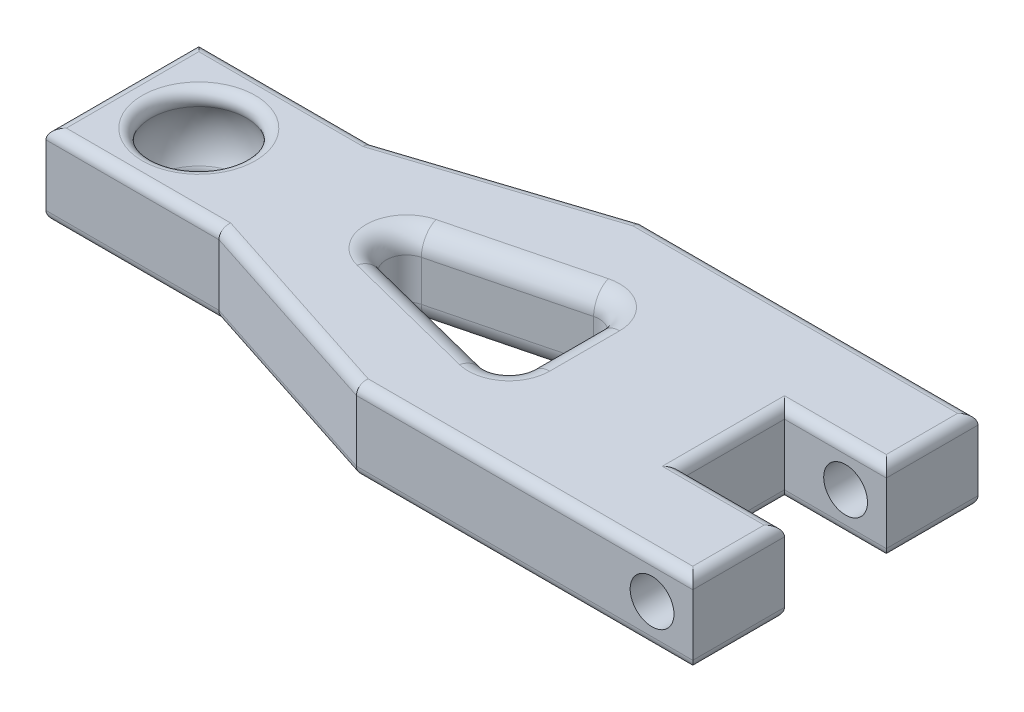
SolidWorks part; units mm, degrees
ref_plane "Front Plane" through (0, 0, 0) normal (0, 0, 1) x (1, 0, 0)
ref_plane "Top Plane" through (0, 0, 0) normal (0, 1, 0) x (1, 0, 0)
ref_plane "Right Plane" through (0, 0, 0) normal (1, 0, 0) x (0, 0, -1)
sketch "Sketch1" plane through (0, 0, 0) normal (0, 1, 0) x (1, 0, 0)
  line L1 (35, -14) -> (-35, -14)
  line L2 (35, -14) -> (35, 14)
  line L3 (35, 14) -> (-35, 14)
  line L4 (-35, -14) -> (-35, 14)
  dimension "D1" = 70
  dimension "D2" = 28
  dimension "D3" = 14
  dimension "D4" = 14
  dimension "D5" = 35
extrude "Boss-Extrude1" add sketch "Sketch1" along normal blind 8
sketch "Sketch2" plane through (0, 8, 0) normal (0, 1, 0) x (1, 0, 0)
  line L0 (35, -14) -> (35, 14) construction
  line L1 (35, 5) -> (25, 5)
  line L2 (35, 5) -> (35, -5)
  line L3 (35, -5) -> (25, -5)
  line L4 (25, 5) -> (25, -5)
  line L5 (35, 14) -> (-35, 14) construction
  line L6 (-35, -14) -> (35, -14) construction
  dimension "D1" = 10
  dimension "D2" = 10
  dimension "D3" = 9
  dimension "D4" = 9
extrude "Cut-Extrude1" cut sketch "Sketch2" against normal blind 10
sketch "Sketch3" plane through (0, 0, 14) normal (0, 0, 1) x (1, 0, 0)
  line L0 (-35, 8) -> (35, 8) construction
  line L2 (35, 8) -> (35, 0) construction
  circle A0 centre (31, 4) radius 2.15
  dimension "D1" = 4.3
  dimension "D2" = 4
  dimension "D3" = 4
extrude "Cut-Extrude2" cut sketch "Sketch3" against normal through all
sketch "Sketch5" plane through (0, 8, 0) normal (0, 1, 0) x (1, 0, 0)
  line L0 (-18.0224, 7.5) -> (1.9776, 14)
  line L1 (-35, 14) -> (-18.0224, 14)
  line L2 (-35, 14) -> (-35, 7.5)
  line L3 (-35, 7.5) -> (-18.0224, 7.5)
  line L4 (-18.0224, 14) -> (-18.0224, 7.5)
  line L5 (-35, -14) -> (-18.0224, -14)
  line L6 (-35, -14) -> (-35, -7.5)
  line L7 (-35, -7.5) -> (-18.0224, -7.5)
  line L8 (-18.0224, -14) -> (-18.0224, -7.5)
  line L9 (35, 14) -> (-35, 14) construction
  line L10 (-18.0224, -7.5) -> (1.9776, -14)
  line L11 (-35, -14) -> (35, -14) construction
  line L12 (1.9776, -14) -> (-18.0224, -14)
  line L13 (1.9776, 14) -> (-18.0224, 14)
  line M10 (35, 14) -> (-35, 14)
  line M11 (-35, 14) -> (-35, -14)
  line M12 (-35, -14) -> (35, -14)
  dimension "D1" = 15
  dimension "D2" = 6.5
  dimension "D3" = 20
  dimension "D4" = 20
  dimension "D5" = 6.5
extrude "Cut-Extrude4" cut sketch "Sketch5" against normal through all contours L4 L3 M10 M11 | L4 L0 M10 | L10 L8 M12 | L8 L7 M12 M11
sketch "Sketch6" plane through (0, 0, 0) normal (0, 0, 1) x (1, 0, 0)
  line L3 (-35, 0) -> (-18.0224, 0) construction
  line L4 (-35, 8) -> (-18.0224, 8) construction
  line L5 (-27.5, 8) -> (-27.5, 0) construction
  line L6 (-31, 8) -> (-27.5, 8)
  line L8 (-27.5, 8) -> (-27.5, 0)
  line L12 (-31, 0) -> (-27.5, 0)
  arc A1 (-31, 8) -> (-31, 0) centre (-27.5, 4) ccw
  dimension "D1" = 3.5
  dimension "D7" = 3.5
revolve "Cut-Revolve1" cut sketch "Sketch6" angle 360 about L5
fillet "Fillet1" radius 1 26 edges at (-26.5112, 0, 7.5) (-8.0224, 0, 10.75) (18.4888, 0, 14) (35, 0, 9.5) (30, 0, 5) (25, 0, 0) (30, 0, -5) (35, 0, -9.5) (18.4888, 0, -14) (-8.0224, 0, -10.75) (-26.5112, 0, -7.5) (-35, 0, 0) (-27.5, 0, 3.5) (-8.0224, 8, -10.75) (18.4888, 8, -14) (35, 8, -9.5) (30, 8, -5) (25, 8, 0) (30, 8, 5) (35, 8, 9.5) (18.4888, 8, 14) (-8.0224, 8, 10.75) (-26.5112, 8, 7.5) (-35, 8, 0) (-26.5112, 8, -7.5) (-27.5, 8, 3.5)
sketch "Sketch7" plane through (0, 8, 0) normal (0, 1, 0) x (1, 0, 0)
  line L0 (-15.2165, 0) -> (8.3909, -6)
  line L1 (8.3909, -6) -> (8.3909, 6)
  line L2 (8.3909, 6) -> (-15.2165, 0)
  line L4 (1.9776, 14) -> (35, 14) construction
  line L5 (35, -14) -> (1.9776, -14) construction
  line L6 (1.9776, -14) -> (-18.0224, -7.5) construction
  line L8 (-18.0224, 7.5) -> (1.9776, 14) construction
  dimension "D1" = 8
  dimension "D2" = 8
  dimension "D3" = 8
  dimension "D4" = 8
extrude "Cut-Extrude5" cut sketch "Sketch7" against normal blind 10
fillet "Fillet2" radius 2 9 edges at (8.3909, 0, 0) (8.3909, 8, 0) (-3.4128, 0, -3) (-3.4128, 8, -3) (8.3909, 4, -6) (-3.4128, 0, 3) (8.3909, 4, 6) (-3.4128, 8, 3) (-15.2165, 4, 0)
